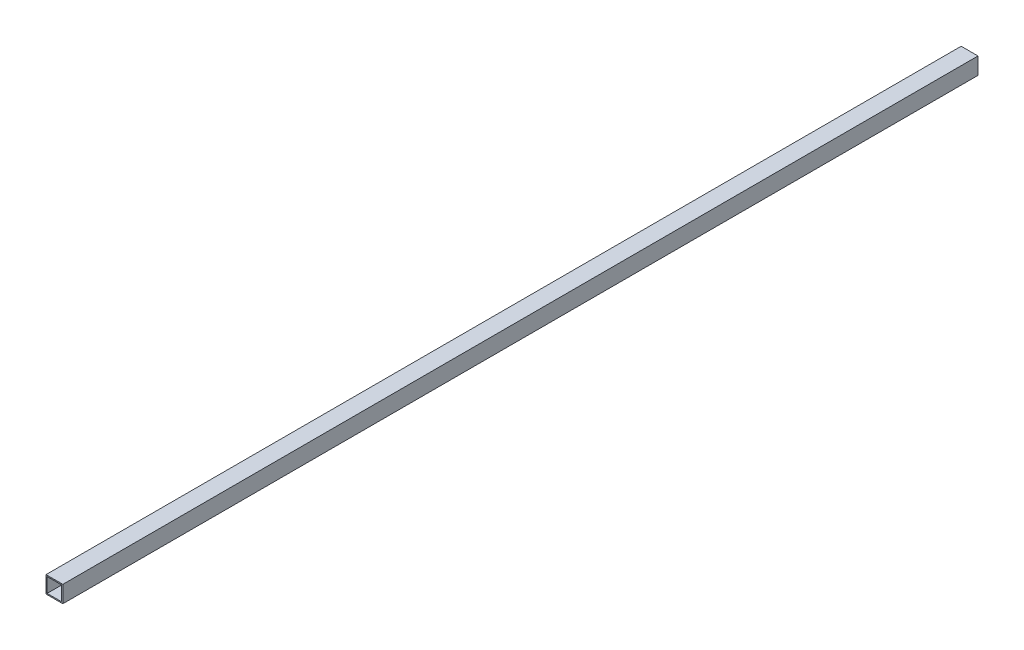
SolidWorks part; units mm, degrees
material "1060 合金"
ref_plane "前视基准面" through (0, 0, 0) normal (0, 0, 1) x (1, 0, 0)
ref_plane "上视基准面" through (0, 0, 0) normal (0, 1, 0) x (1, 0, 0)
ref_plane "右视基准面" through (0, 0, 0) normal (1, 0, 0) x (0, 0, -1)
other "Configuration Table"
sketch "草图1" plane through (0, 0, 0) normal (0, 0, 1) x (1, 0, 0)
  line L1 (0, 0) -> (15, 0)
  line L2 (0, 0) -> (0, -15)
  line L3 (0, -15) -> (15, -15)
  line L4 (15, 0) -> (15, -15)
  dimension "D1" = 15
  dimension "D2" = 15
extrude "拉伸-薄壁1" add sketch "草图1" along normal blind 815 thin
